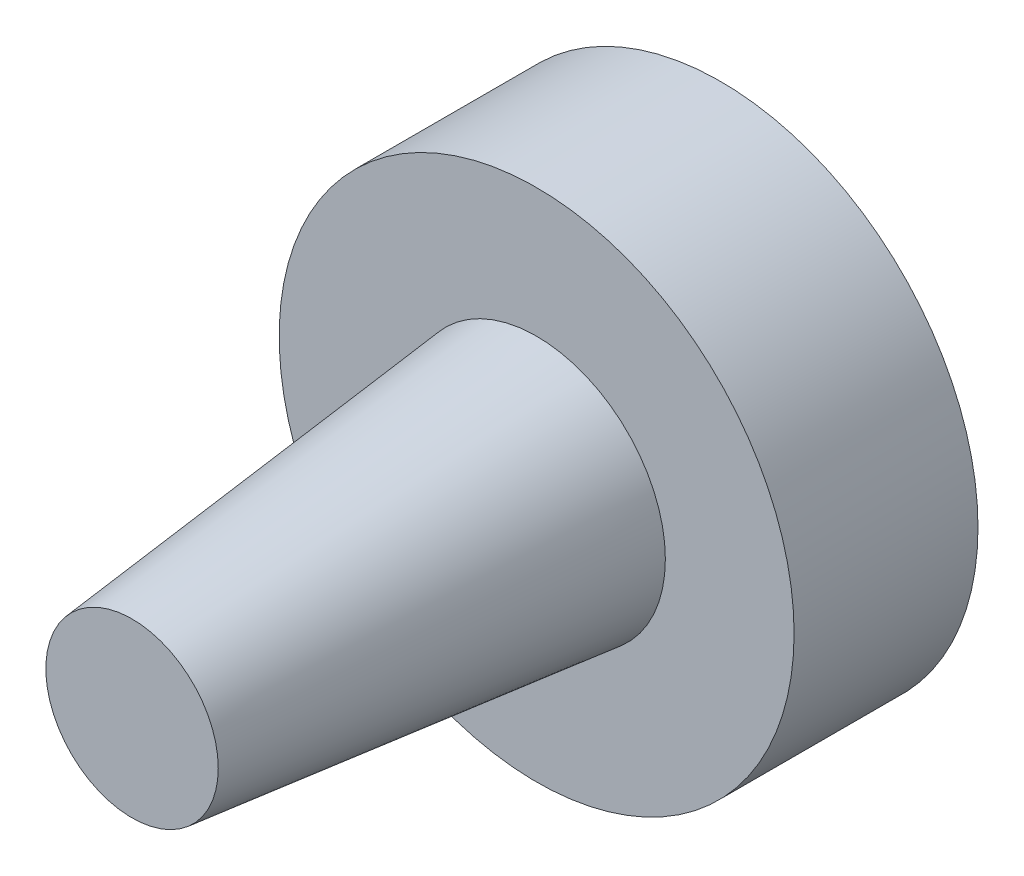
SolidWorks part; units mm, degrees
ref_plane "Front Plane" through (0, 0, 0) normal (0, 0, 1) x (1, 0, 0)
ref_plane "Top Plane" through (0, 0, 0) normal (0, 1, 0) x (1, 0, 0)
ref_plane "Right Plane" through (0, 0, 0) normal (1, 0, 0) x (0, 0, -1)
sketch "Sketch1" plane through (0, 0, 0) normal (0, 0, 1) x (1, 0, 0)
  circle A0 centre (0, 0) radius 7
  dimension "D1" = 14
extrude "Boss-Extrude1" add sketch "Sketch1" along normal blind 5
sketch "Sketch2" plane through (0, 0, 5) normal (0, 0, 1) x (1, 0, 0)
  circle A0 centre (0, 0) radius 3.5
  dimension "D1" = 7
extrude "Boss-Extrude2" add sketch "Sketch2" along normal blind 11 draft 6
